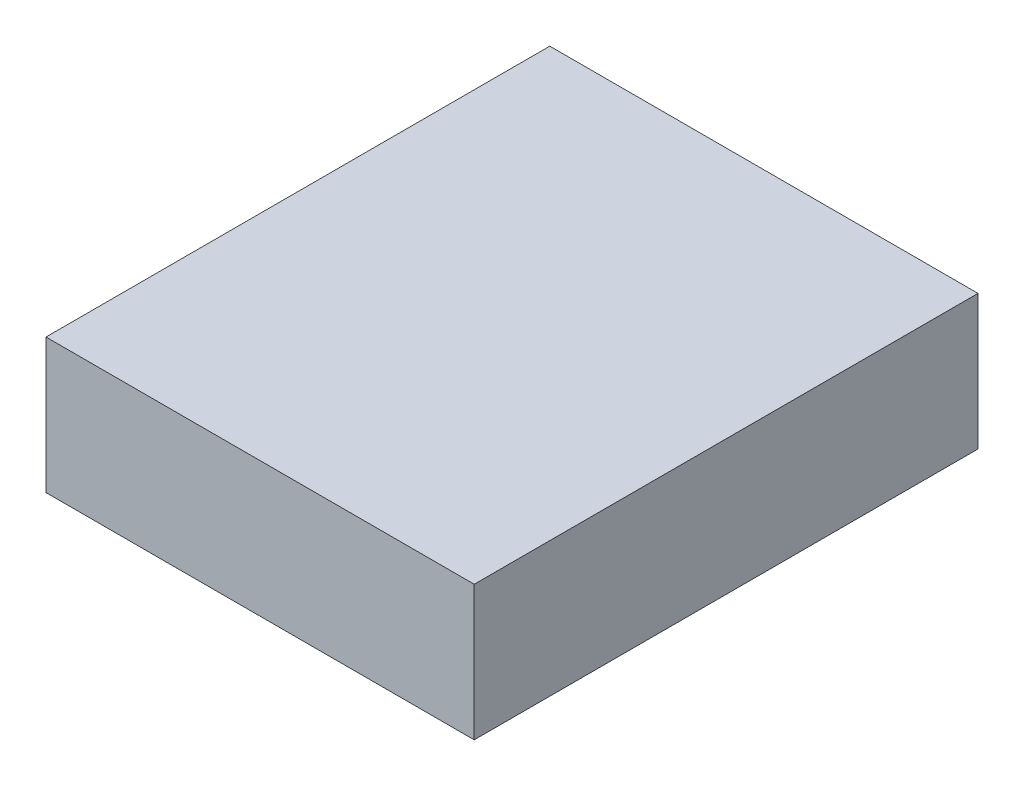
SolidWorks part; units mm, degrees
ref_plane "Front Plane" through (0, 0, 0) normal (0, 0, 1) x (1, 0, 0)
ref_plane "Top Plane" through (0, 0, 0) normal (0, 1, 0) x (1, 0, 0)
ref_plane "Right Plane" through (0, 0, 0) normal (1, 0, 0) x (0, 0, -1)
sketch "Sketch1" plane through (0, 0, 0) normal (0, 1, 0) x (1, 0, 0)
  line L1 (-17, -20) -> (17, -20)
  line L2 (-17, -20) -> (-17, 20)
  line L3 (-17, 20) -> (17, 20)
  line L4 (17, -20) -> (17, 20)
  line L5 (-17, -20) -> (17, 20) construction
  line L6 (-17, 20) -> (17, -20) construction
  point P0 (0, 0)
  dimension "D1" = 34
  dimension "D2" = 40
extrude "Boss-Extrude1" add sketch "Sketch1" along normal blind 10.7
